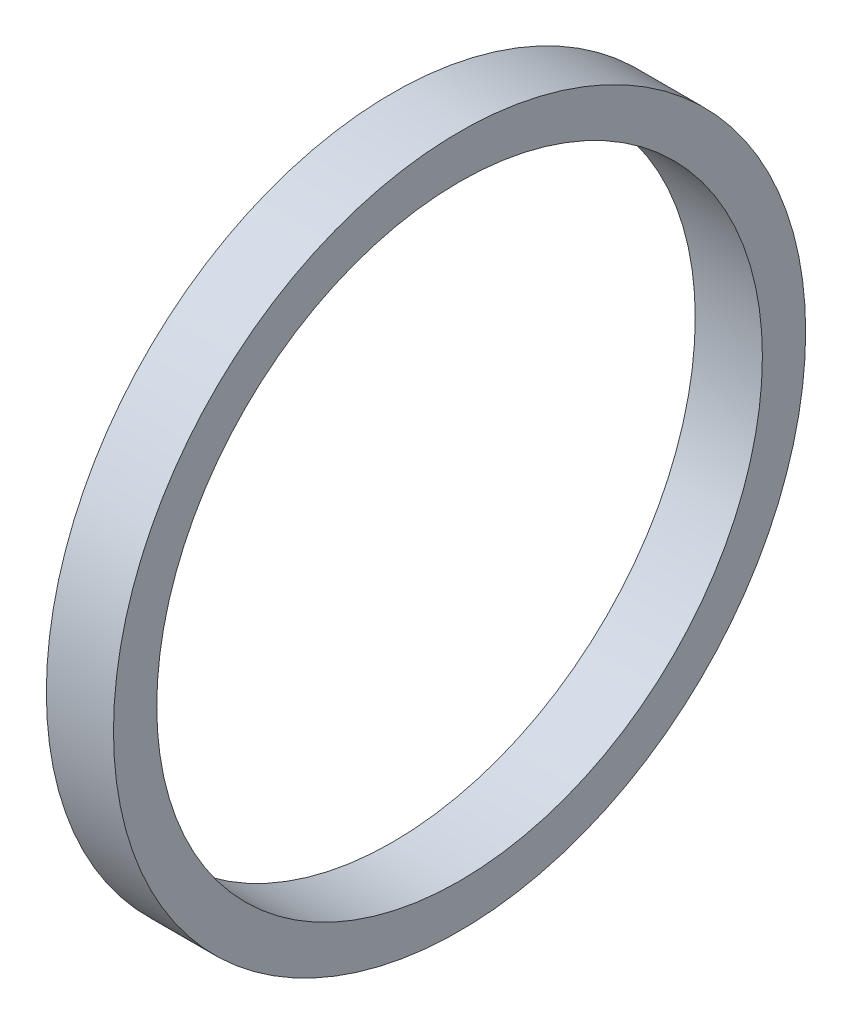
SolidWorks part; units mm, degrees
ref_plane "Front Plane" through (0, 0, 0) normal (0, 0, 1) x (1, 0, 0)
ref_plane "Top Plane" through (0, 0, 0) normal (0, 1, 0) x (1, 0, 0)
ref_plane "Right Plane" through (0, 0, 0) normal (1, 0, 0) x (0, 0, -1)
sketch "Sketch1" plane through (0, 0, 0) normal (1, 0, 0) x (0, 0, -1)
  circle A0 centre (0, 0) radius 12.7
  circle A1 centre (0, 0) radius 11.1125
  dimension "D1" = 25.4
  dimension "D2" = 22.225
extrude "Boss-Extrude1" add sketch "Sketch1" along normal blind 2.4638
